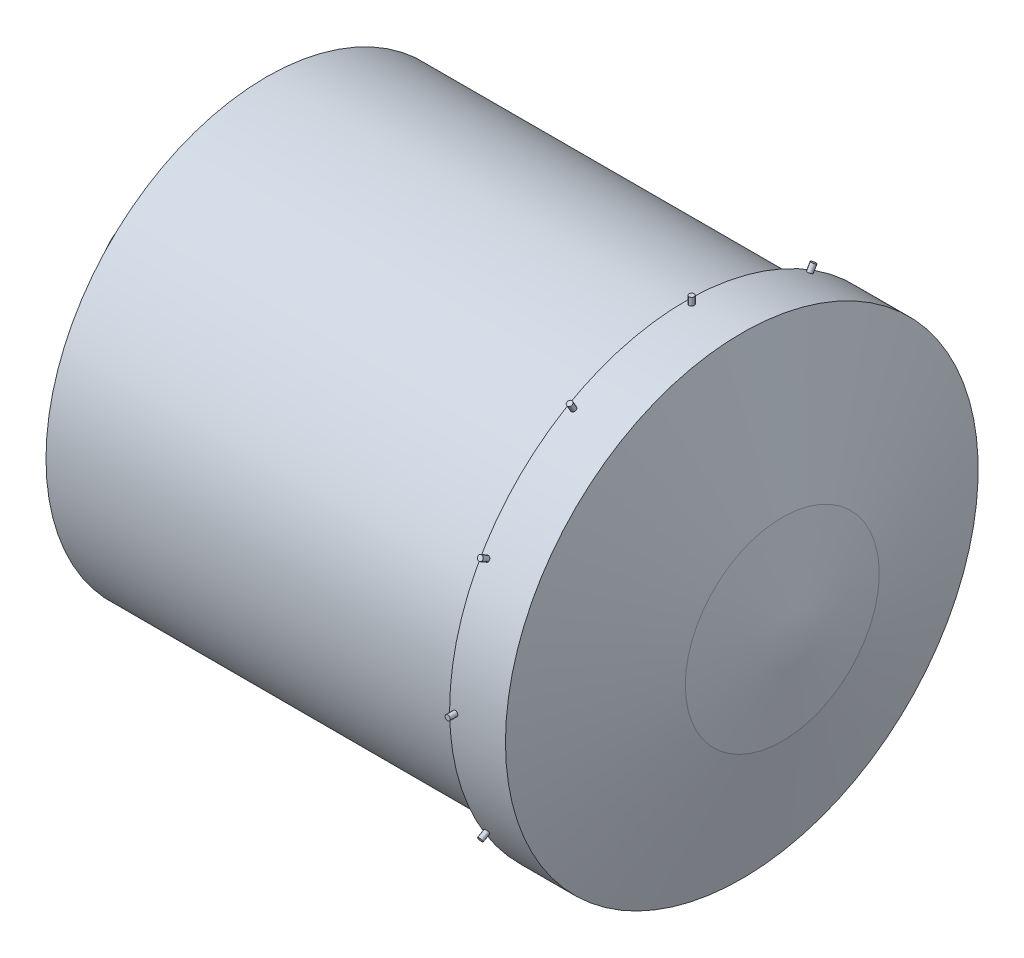
SolidWorks part; units mm, degrees
ref_plane "Front Plane" through (0, 0, 0) normal (0, 0, 1) x (1, 0, 0)
ref_plane "Top Plane" through (0, 0, 0) normal (0, 1, 0) x (1, 0, 0)
ref_plane "Right Plane" through (0, 0, 0) normal (1, 0, 0) x (0, 0, -1)
sketch "Sketch2" plane through (0, 0, 0) normal (0, 0, 1) x (1, 0, 0)
  line L0 (-425.5655, 0) -> (425.5655, 0) construction
  line L1 (-425.5655, 0) -> (-425.5655, 56.5978)
  line L2 (-425.5655, 56.5978) -> (-321.2497, 56.5978)
  line L3 (-321.2497, 56.5978) -> (-321.2497, 105.3732)
  line L4 (-321.2497, 108.5942) -> (-298.7026, 108.5942)
  line L5 (-298.7026, 108.5942) -> (-298.7026, 271.0254)
  line L6 (-298.7026, 271.0254) -> (-297.7824, 270.5652)
  line L7 (-297.7824, 270.5652) -> (-270.1737, 270.5652)
  line L8 (-270.1737, 270.5652) -> (-270.1737, 295.413)
  line L9 (358.3843, 173.0145) -> (358.3843, 322.2086)
  line L10 (358.3843, 322.2086) -> (-270.1737, 322.2086)
  line L11 (358.3843, 173.0145) -> (381.8517, 173.0145)
  line L12 (381.8517, 173.0145) -> (381.8517, 154.1486)
  line L13 (381.8517, 154.1486) -> (403.9387, 154.1486)
  line L14 (403.9387, 154.1486) -> (403.9387, 122.3986)
  line L15 (403.9387, 122.3986) -> (425.5655, 122.3986)
  line L16 (425.5655, 122.3986) -> (425.5655, 0)
  line L17 (-321.2497, 108.5942) -> (-321.2497, 105.3732)
  line L18 (425.5655, 0) -> (-425.5655, 0)
  line L19 (-270.1737, 322.2086) -> (-270.1737, 295.413)
  point P4 (0, 0)
revolve "Revolve1" add sketch "Sketch2" angle 360 about L0
sketch "Sketch3" plane through (-425.5655, 0, 0) normal (-1, 0, 0) x (0, 0, 1)
  circle A1 centre (0, 0) radius 56.5978
  circle A2 centre (0, 0) radius 56.5978
  dimension "D1" = 0
extrude "Boss-Extrude1" add sketch "Sketch3" along normal blind 33
sketch "Sketch4" plane through (-458.5655, 0, 0) normal (-1, 0, 0) x (0, 0, 1)
  line L0 (-9.7187, 55.7572) -> (-9.7187, 10.8016)
  line L1 (-9.7187, 10.8016) -> (3.1051, 10.8016)
  line L2 (3.1051, 10.8016) -> (3.1051, 56.5126)
  circle A0 centre (0, 0) radius 56.5978 construction
  circle A3 centre (0, 0) radius 56.5978
  arc A4 (3.1051, 56.5126) -> (-9.7187, 55.7572) centre (0, 0) ccw
  dimension "D2" = 0
extrude "Cut-Extrude1" cut sketch "Sketch4" against normal blind 59
ref_plane "Plane1" through (86, 0, 0) normal (1, 0, 0) x (0, 0, -1)
ref_plane "Plane2" through (84, 0, 0) normal (1, 0, 0) x (0, 0, -1)
sketch "Sketch5" plane through (358.3843, 0, 0) normal (1, 0, 0) x (0, 0, -1)
  line L0 (0, 338.6282) -> (0, 305.7891) construction
  line L1 (-12.44, 338.6282) -> (12.44, 338.6282)
  line L2 (0, 322.2086) -> (28.6067, 322.2086) construction
  line L3 (-12.44, 305.7891) -> (12.44, 305.7891)
  line L4 (-12.44, 338.6282) -> (-12.44, 305.7891)
  line L5 (12.44, 338.6282) -> (12.44, 305.7891)
  circle A1 centre (0, 0) radius 322.2086
  arc A2 (12.44, 321.9684) -> (-12.44, 321.9684) centre (0, 0) ccw
  point P7 (0, 322.2086)
  point P10 (0, 338.6282)
  dimension "D1" = 0
extrude "Boss-Extrude2" add sketch "Sketch5" against normal blind 15.748 contours L4 L3 L5 L1
sketch "Sketch6" plane through (0, 338.6282, 0) normal (0, 1, 0) x (1, 0, 0)
  circle A0 centre (350.8537, 0) radius 3.7857
extrude "Boss-Extrude3" add sketch "Sketch6" along normal blind 17.78
pattern_circular "CirPattern1" count 12 over 360 about axis through (0, 0, 0) along (1, 0, 0) of "Boss-Extrude3", "Boss-Extrude2"
sketch "Sketch7" plane through (0, 0, 0) normal (0, 0, 1) x (1, 0, 0)
  line L0 (-501.8284, 0) -> (496.9088, 0) construction
  line L1 (342.6363, 338.6282) -> (417.278, 338.6282)
  line L2 (417.278, 338.6282) -> (475.1151, 141.6589)
  line L3 (475.1151, 141.6589) -> (496.9088, 0)
  line L4 (342.6363, 345.326) -> (424.1978, 345.326)
  line L5 (424.1978, 345.326) -> (483.3033, 141.6589)
  line L6 (483.3033, 141.6589) -> (509.179, 0)
  line L7 (496.9088, 0) -> (509.179, 0)
  line L8 (342.6363, 345.326) -> (342.6363, 338.6282)
revolve "Revolve2" add sketch "Sketch7" angle 360 about L0
ref_plane "Plane3" through (563.88, 0, 0) normal (1, 0, 0) x (0, 0, -1)
sketch "Sketch8" plane through (563.88, 0, 0) normal (1, 0, 0) x (0, 0, -1)
  line L0 (-394.5433, 0) -> (393.4681, 0) construction
  line L1 (0, 393.6727) -> (0, -390.9829) construction
